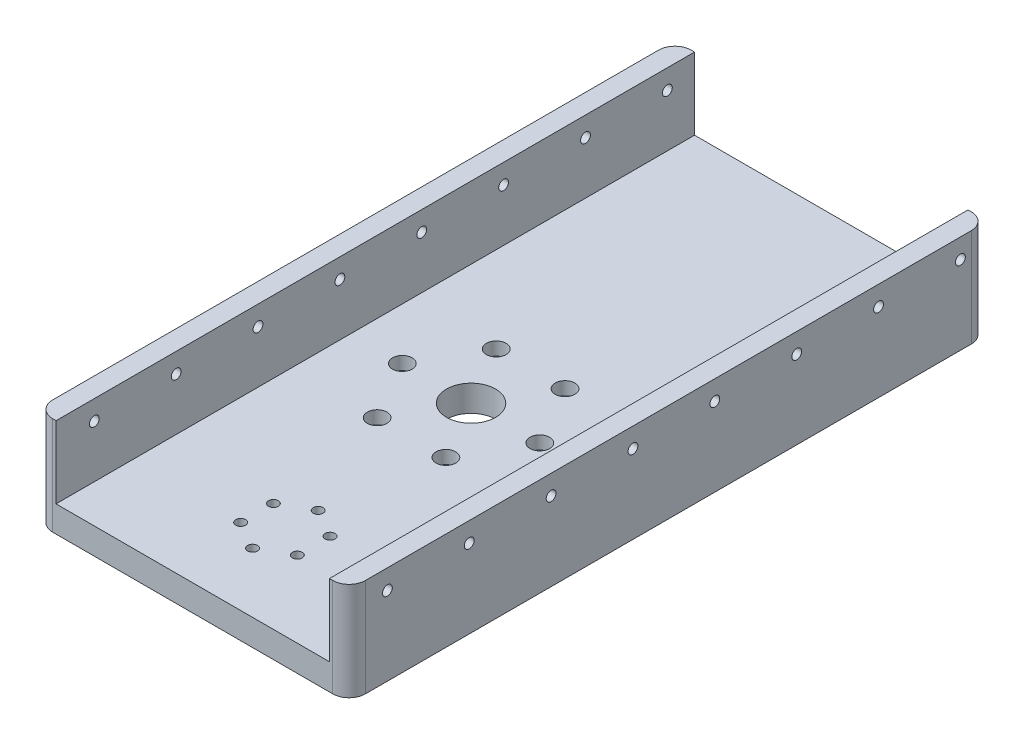
SolidWorks part; units mm, degrees
ref_plane "Front Plane" through (0, 0, 0) normal (0, 0, 1) x (1, 0, 0)
ref_plane "Top Plane" through (0, 0, 0) normal (0, 1, 0) x (1, 0, 0)
ref_plane "Right Plane" through (0, 0, 0) normal (1, 0, 0) x (0, 0, -1)
sketch "Sketch1" plane through (0, 0, 0) normal (0, 1, 0) x (1, 0, 0)
  line L1 (0, 0) -> (89.5, 0)
  line L2 (0, 0) -> (0, 125)
  line L3 (0, 125) -> (89.5, 125)
  line L4 (89.5, 0) -> (89.5, 125)
  dimension "D1" = 89.5
  dimension "D2" = 125
extrude "Boss-Extrude1" add sketch "Sketch1" along normal blind 8
sketch "Sketch2" plane through (0, 8, 0) normal (0, 1, 0) x (-1, 0, 0)
  line L0 (-89.5, -90) -> (-36.75, -90) construction
  line L1 (-89.5, 0) -> (-89.5, -125) construction
  line L2 (-36.75, -90) -> (-57.75, -90) construction
  line L3 (-89.5, -125) -> (-89.5, -90) construction
  circle A0 centre (-36.75, -90) radius 7.5
  circle A1 centre (-57.75, -90) radius 3
  circle A20 centre (-47.25, -71.8135) radius 3
  circle A21 centre (-26.25, -71.8135) radius 3
  circle A22 centre (-15.75, -90) radius 3
  circle A23 centre (-26.25, -108.1865) radius 3
  circle A24 centre (-47.25, -108.1865) radius 3
  point P21 (-36, -83.9378)
  point P22 (-40.5, -88.2679)
  point P23 (-37.5, -96.9282)
  point P24 (-34.75, -89.567)
  point P25 (-34, -89.134)
  point P26 (-35.5, -89.134)
  point P27 (-35, -105.5885)
  point P28 (-36, -88.2679)
  point P29 (-42.625, -76.7931)
  point P30 (-38.75, -83.9378)
  point P31 (-37.125, -86.3194)
  point P32 (-40.75, -87.4019)
  point P33 (-36, -88.701)
  point P35 (-36.75, -90)
  dimension "D4" = 15
  dimension "D6" = 6
  dimension "D1" = 52.75
  dimension "D2" = 21
  dimension "D3" = 35
  dimension "D5" = 0
  dimension "D7" = 6
extrude "Cut-Extrude1" cut sketch "Sketch2" against normal blind 4
sketch "Sketch3" plane through (0, 4, 0) normal (0, 1, 0) x (1, 0, 0)
  circle A0 centre (36.75, 90) radius 7.5
  dimension "D1" = 15
extrude "Cut-Extrude2" cut sketch "Sketch3" against normal through all
sketch "Sketch4" plane through (89.5, 0, 0) normal (1, 0, 0) x (0, 0, -1)
  line L0 (125, 8) -> (125, 0) construction
  line L1 (0, 8) -> (125, 8)
  line L2 (0, 8) -> (0, 30)
  line L3 (0, 30) -> (125, 30)
  line L4 (125, 8) -> (125, 30)
  line L5 (11.6922, 30) -> (11.6922, 24) construction
  circle A0 centre (11.6922, 24) radius 1.5
  circle A1 centre (36.6922, 24) radius 1.5
  circle A2 centre (61.6922, 24) radius 1.5
  circle A3 centre (86.6922, 24) radius 1.5
  circle A4 centre (111.6922, 24) radius 1.5
  dimension "D4" = 3
  dimension "D1" = 22
  dimension "D2" = 0
  dimension "D3" = 6
  dimension "D5" = 5
extrude "Boss-Extrude2" add sketch "Sketch4" against normal blind 6 contours L2 L1 L4 L3
sketch "Sketch5" plane through (0, 8, 0) normal (0, 1, 0) x (-1, 0, 0)
  circle A0 centre (-57.75, -90) radius 1.5
  circle A56 centre (-47.25, -71.8135) radius 1.5
  circle A57 centre (-26.25, -71.8135) radius 1.5
  circle A58 centre (-15.75, -90) radius 1.5
  circle A59 centre (-26.25, -108.1865) radius 1.5
  circle A60 centre (-47.25, -108.1865) radius 1.5
  point P16 (-36, -96.0622)
  point P17 (-40.5, -91.7321)
  point P18 (-37.5, -83.0718)
  point P19 (-34, -90.866)
  point P20 (-34.7211, -90.383)
  point P21 (-34.7162, -90)
  point P22 (-22.2111, -90)
  point P23 (-37.125, -93.6806)
  point P24 (-40.75, -92.5981)
  point P25 (-36, -91.299)
  point P26 (-36.75, -90)
  point P27 (-38.75, -83.9378)
  dimension "D1" = 3
  dimension "D2" = 6
extrude "Cut-Extrude3" cut sketch "Sketch5" against normal through all
sketch "Sketch8" plane through (0, 0, 0) normal (-1, 0, 0) x (0, 0, 1)
  line L1 (-125, 0) -> (0, 0)
  line L2 (-125, 0) -> (-125, 30)
  line L3 (-125, 30) -> (0, 30)
  line L4 (0, 0) -> (0, 30)
  dimension "D1" = 30
extrude "Boss-Extrude3" add sketch "Sketch8" along normal blind 6
sketch "Sketch11" plane through (0, 0, -125) normal (0, 0, -1) x (-1, 0, 0)
  line L0 (6, 30) -> (0, 30)
  line L1 (0, 30) -> (0, 8)
  line L2 (0, 8) -> (-83.5, 8)
  line L3 (-83.5, 8) -> (-83.5, 30)
  line L4 (-83.5, 30) -> (-89.5, 30)
  line L5 (-89.5, 30) -> (-89.5, 0)
  line L6 (-89.5, 0) -> (6, 0)
  line L7 (6, 0) -> (6, 30)
extrude "Boss-Extrude4" add sketch "Sketch11" along normal blind 70
sketch "Sketch9" plane through (0, 0, 0) normal (1, 0, 0) x (0, 0, -1)
  circle A0 centre (11.6922, 24) radius 1.5
  circle A1 centre (36.6922, 24) radius 1.5
  circle A2 centre (61.6922, 24) radius 1.5
  circle A3 centre (86.6922, 24) radius 1.5
  circle A4 centre (111.6922, 24) radius 1.5
  circle A5 centre (136.6922, 24) radius 1.5
  circle A6 centre (161.6922, 24) radius 1.5
  circle A7 centre (186.6922, 24) radius 1.5
  dimension "D1" = 3
  dimension "D3" = 2
  dimension "D2" = 5
  dimension "D4" = 3
extrude "Cut-Extrude5" cut sketch "Sketch9" along normal through all both and the other way through all
fillet "Fillet2" radius 5 4 edges at (89.5, 15, 0) (-6, 15, 0) (89.5, 15, -195) (-6, 15, -195)
sketch "Sketch12" plane through (0, 8, 0) normal (0, 1, 0) x (1, 0, 0)
  line L0 (41.75, 0) -> (41.75, 28.29) construction
  line L1 (0, 0) -> (83.5, 0) construction
  circle A0 centre (41.75, 18.29) radius 1.5
  circle A11 centre (33.0897, 23.29) radius 1.5
  circle A12 centre (33.0897, 33.29) radius 1.5
  circle A13 centre (41.75, 38.29) radius 1.5
  circle A14 centre (50.4103, 33.29) radius 1.5
  circle A15 centre (50.4103, 23.29) radius 1.5
  point P19 (40.25, 29.589)
  point P20 (41.375, 28.9395)
  point P21 (41.75, 28.29)
  dimension "D4" = 3
  dimension "D1" = 28.29
  dimension "D2" = 6
  dimension "D3" = 10
extrude "Cut-Extrude6" cut sketch "Sketch12" against normal through all
